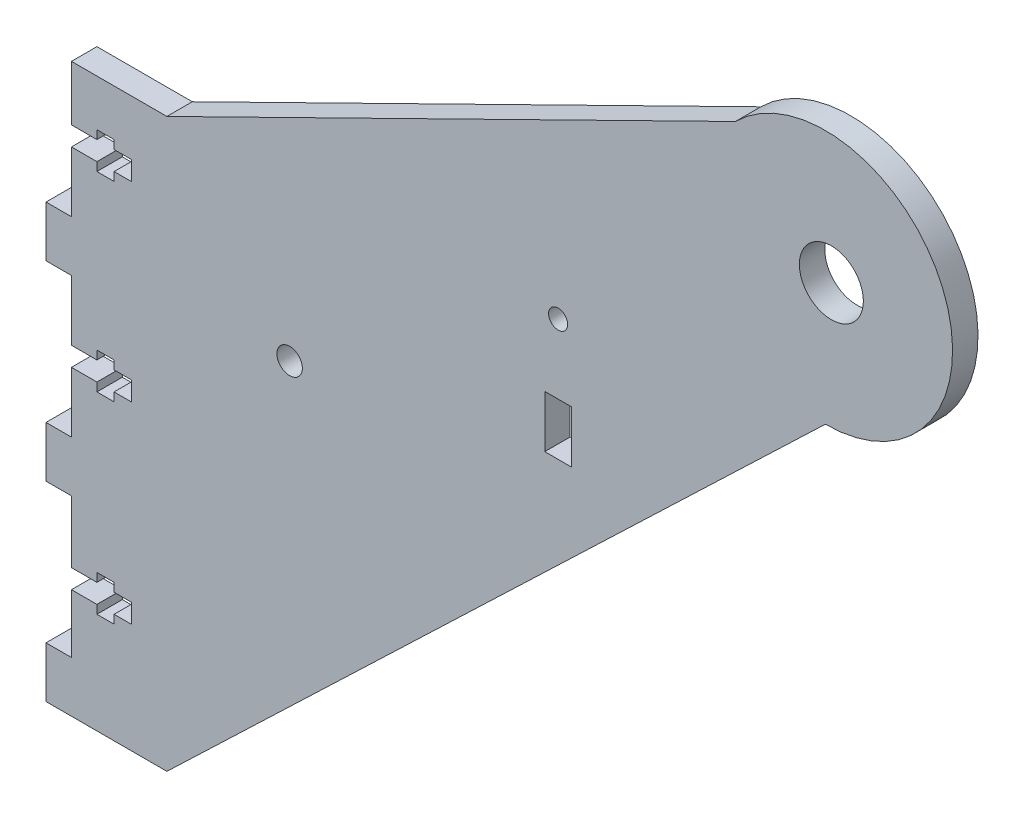
SolidWorks part; units mm, degrees
ref_plane "前视基准面" through (0, 0, 0) normal (0, 0, 1) x (1, 0, 0)
ref_plane "上视基准面" through (0, 0, 0) normal (0, 1, 0) x (1, 0, 0)
ref_plane "右视基准面" through (0, 0, 0) normal (1, 0, 0) x (0, 0, -1)
sketch "草图1" plane through (0, 0, 0) normal (0, 0, 1) x (1, 0, 0)
  line L0 (-3.1612, -22.1136) -> (0.8388, -22.1136)
  line L1 (0.8388, -22.1136) -> (0.8388, -23.4636)
  line L2 (0.8388, -23.4636) -> (3.5388, -23.4636)
  line L3 (3.5388, -23.4636) -> (3.5388, -22.1136)
  line L4 (3.5388, -22.1136) -> (6.2388, -22.1136)
  line L5 (6.2388, -22.1136) -> (6.2388, -19.1136)
  line L6 (-3.1612, -20.6136) -> (-4.469, -20.6136) construction
  line L7 (-3.1612, -22.1136) -> (-3.1612, -19.1136) construction
  line L8 (3.5388, -17.7636) -> (3.5388, -19.1136)
  line L9 (0.8388, -19.1136) -> (0.8388, -17.7636)
  line L10 (3.5388, -19.1136) -> (6.2388, -19.1136)
  line L11 (0.8388, -17.7636) -> (3.5388, -17.7636)
  line L12 (-3.1612, -19.1136) -> (0.8388, -19.1136)
  line L13 (-3.1612, -39.3444) -> (-7.1612, -39.3444)
  line L14 (-7.1612, -39.3444) -> (-7.1612, -31.3444)
  line L15 (-7.1612, -31.3444) -> (-3.1612, -31.3444)
  line L16 (-3.1612, -31.3444) -> (-3.1612, -22.1136)
  line L17 (-7.1612, -35.3444) -> (-5.4582, -35.3444) construction
  line L18 (6.8829, 39.3864) -> (3.9614, 39.3864) construction
  line L19 (-5.7171, 24.3864) -> (-4.0142, 24.3864) construction
  line L20 (6.2388, 9.6556) -> (-2.6612, 9.6556) construction
  line L21 (-5.7171, -5.6136) -> (-4.0142, -5.6136) construction
  line L22 (-3.1612, -22.1136) -> (0.8388, -22.1136)
  line L23 (0.8388, -22.1136) -> (0.8388, -23.4636)
  line L24 (0.8388, -23.4636) -> (3.5388, -23.4636)
  line L25 (3.5388, -23.4636) -> (3.5388, -22.1136)
  line L26 (3.5388, -22.1136) -> (6.2388, -22.1136)
  line L27 (3.5388, -17.7636) -> (3.5388, -19.1136)
  line L28 (0.8388, -19.1136) -> (0.8388, -17.7636)
  line L29 (3.5388, -19.1136) -> (6.2388, -19.1136)
  line L30 (-3.1612, -22.1136) -> (0.8388, -22.1136)
  line L31 (0.8388, -23.4636) -> (3.5388, -23.4636)
  line L32 (3.5388, -22.1136) -> (6.2388, -22.1136)
  line L33 (0.8388, -22.1136) -> (0.8388, -23.4636)
  line L34 (3.5388, -23.4636) -> (3.5388, -22.1136)
  line L35 (3.5388, -19.1136) -> (6.2388, -19.1136)
  line L36 (3.5388, -17.7636) -> (3.5388, -19.1136)
  line L37 (0.8388, -17.7636) -> (3.5388, -17.7636)
  line L38 (0.8388, -19.1136) -> (0.8388, -17.7636)
  line L39 (-3.1612, -19.1136) -> (0.8388, -19.1136)
  line L40 (0.8388, -17.7636) -> (3.5388, -17.7636)
  line L41 (-3.1612, -19.1136) -> (0.8388, -19.1136)
  line L42 (0.8388, 36.8056) -> (3.5388, 36.8056)
  line L43 (3.5388, 38.1556) -> (6.2388, 38.1556)
  line L44 (0.8388, 38.1556) -> (0.8388, 36.8056)
  line L45 (3.5388, 36.8056) -> (3.5388, 38.1556)
  line L46 (6.2388, 41.1556) -> (6.2388, 38.1556)
  line L47 (3.5388, 41.1556) -> (6.2388, 41.1556)
  line L48 (3.5388, 42.5056) -> (3.5388, 41.1556)
  line L49 (0.8388, 42.5056) -> (3.5388, 42.5056)
  line L50 (0.8388, 41.1556) -> (0.8388, 42.5056)
  line L51 (0.8388, 41.1556) -> (-3.1612, 41.1556)
  line L52 (0.8388, 38.1556) -> (-3.1612, 38.1556)
  line L53 (-3.1612, 28.6556) -> (-3.1612, 38.1556)
  line L54 (-3.1612, 20.6556) -> (-7.1612, 20.6556)
  line L55 (-7.1612, 20.6556) -> (-7.1612, 28.6556)
  line L56 (-7.1612, 28.6556) -> (-3.1612, 28.6556)
  line L57 (-3.1612, 8.1556) -> (-3.1612, -1.3444)
  line L58 (0.8388, 8.1556) -> (-3.1612, 8.1556)
  line L59 (0.8388, 11.1556) -> (-3.1612, 11.1556)
  line L60 (-3.1612, 20.6556) -> (-3.1612, 11.1556)
  line L61 (0.8388, 8.1556) -> (0.8388, 6.8056)
  line L62 (0.8388, 6.8056) -> (3.5388, 6.8056)
  line L63 (3.5388, 6.8056) -> (3.5388, 8.1556)
  line L64 (3.5388, 8.1556) -> (6.2388, 8.1556)
  line L65 (6.2388, 8.1556) -> (6.2388, 11.1556)
  line L66 (3.5388, 12.5056) -> (3.5388, 11.1556)
  line L67 (0.8388, 11.1556) -> (0.8388, 12.5056)
  line L68 (3.5388, 11.1556) -> (6.2388, 11.1556)
  line L69 (0.8388, 12.5056) -> (3.5388, 12.5056)
  line L70 (-3.1612, -9.3444) -> (-3.1612, -19.1136)
  line L71 (-7.1612, -9.3444) -> (-3.1612, -9.3444)
  line L72 (-7.1612, -1.3444) -> (-7.1612, -9.3444)
  line L73 (-3.1612, -1.3444) -> (-7.1612, -1.3444)
  line L74 (-3.1612, -22.1136) -> (0.8388, -22.1136)
  line L75 (0.8388, -23.4636) -> (3.5388, -23.4636)
  line L76 (3.5388, -22.1136) -> (6.2388, -22.1136)
  line L77 (0.8388, -22.1136) -> (0.8388, -23.4636)
  line L78 (3.5388, -23.4636) -> (3.5388, -22.1136)
  line L79 (3.5388, -19.1136) -> (6.2388, -19.1136)
  line L80 (3.5388, -17.7636) -> (3.5388, -19.1136)
  line L81 (0.8388, -17.7636) -> (3.5388, -17.7636)
  line L82 (0.8388, -19.1136) -> (0.8388, -17.7636)
  line L83 (-3.1612, -19.1136) -> (0.8388, -19.1136)
  line L84 (-3.1612, 41.1556) -> (-3.1612, 49.8072)
  line L85 (6.2388, -22.1136) -> (11.8388, -22.1136) construction
  line L86 (11.8388, -39.3444) -> (11.8388, 49.8072) construction
  line L87 (82.4077, 112.5867) -> (115.3388, 79.6556) construction
  line L88 (-4.9582, 9.6556) -> (5.1418, 9.6556) construction
  line L89 (11.8388, -39.3444) -> (-3.1612, -39.3444)
  line L90 (115.3388, 79.6556) -> (152.9327, 42.0617) construction
  line L91 (116.2829, 28.2764) -> (116.2829, 79.3864) construction
  line L92 (5.1418, 9.6556) -> (115.3388, 79.6556) construction
  line L93 (101.1967, 93.7977) -> (11.8388, 49.8072)
  line L94 (11.8388, 49.8072) -> (-3.1612, 49.8072)
  line L95 (11.8388, -39.3444) -> (115.3388, 59.6556)
  line L96 (73.3388, 52.9761) -> (73.3388, 37.9761) construction
  line L102 (75.4388, 42.0761) -> (71.2388, 42.0761)
  line L103 (75.4388, 42.0761) -> (75.4388, 33.8761)
  line L104 (75.4388, 33.8761) -> (71.2388, 33.8761)
  line L105 (71.2388, 42.0761) -> (71.2388, 33.8761)
  line L106 (75.4388, 42.0761) -> (71.2388, 33.8761) construction
  line L107 (75.4388, 33.8761) -> (71.2388, 42.0761) construction
  circle A3 centre (116.2829, 79.3864) radius 5.03
  arc A6 (115.3388, 59.6556) -> (101.1967, 93.7977) centre (115.3388, 79.6556) ccw
  circle A7 centre (115.3388, 79.6556) radius 20 construction
  circle A8 centre (73.3388, 52.9761) radius 1.5
  circle A11 centre (31.134, 26.1665) radius 2
  point P11 (-3.8151, -20.6136)
  point P27 (-4.8657, -5.6136)
  dimension "D8" = 10.06
  dimension "D9" = 118.5
  dimension "D12" = 4
  dimension "D13" = 50
  dimension "D14" = 8
  dimension "D10" = 45
  dimension "D11" = 42
  dimension "D1" = 4
  dimension "D2" = 15
  dimension "D3" = 2.7
  dimension "D4" = 1.35
  dimension "D5" = 1.5
  dimension "D6" = 9.5
  dimension "D7" = 15
  dimension "D15" = 15
  dimension "D16" = 8.2
  dimension "D17" = 4
  dimension "D18" = 4.2
  dimension "D19" = 30
  dimension "D20" = 70
extrude "凸台-拉伸1" add sketch "草图1" along normal blind 4
sketch "草图2" plane through (-3.1612, 0, 0) normal (-1, 0, 0) x (0, 0, 1)
  line L0 (2, -19.1136) -> (2, -22.1136)
  line L1 (4, -19.1136) -> (0, -19.1136) construction
  line L2 (4, -22.1136) -> (0, -22.1136) construction
  circle A0 centre (2, -20.6136) radius 1.5
